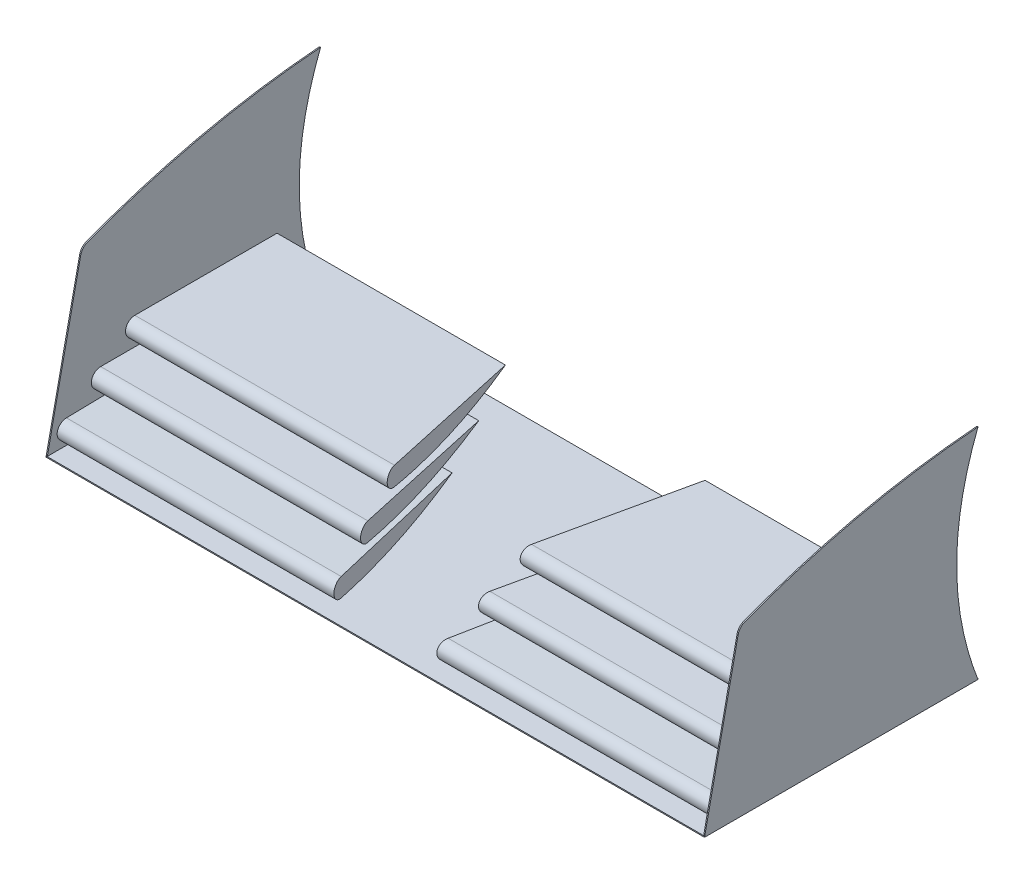
SolidWorks part; units mm, degrees
ref_plane "Front Plane" through (0, 0, 0) normal (0, 0, 1) x (1, 0, 0)
ref_plane "Top Plane" through (0, 0, 0) normal (0, 1, 0) x (1, 0, 0)
ref_plane "Right Plane" through (0, 0, 0) normal (1, 0, 0) x (0, 0, -1)
sketch "Sketch1" plane through (0, 0, 0) normal (1, 0, 0) x (0, 0, -1)
  line L1 (0, 0) -> (635, 0)
  line L2 (0, 0) -> (0, 508)
  line L3 (0, 508) -> (635, 508)
  line L4 (635, 0) -> (635, 508)
  dimension "D1" = 508
  dimension "D2" = 635
extrude "Boss-Extrude1" add sketch "Sketch1" along normal blind 2.54 from offset 762
mirror "Mirror2" about plane through (0, 0, 0) normal (1, 0, 0) of bodies 101
sketch "Sketch2" plane through (0, 0, 0) normal (1, 0, 0) x (0, 0, -1)
  line L0 (635, 508) -> (635, 0)
  spline S0 degree 2 poles (635, 508) (535.9785, 253.9497) (635, 0) knots 0 0 0 1 1 1
extrude "Cut-Extrude1" cut sketch "Sketch2" against normal through all both and the other way through all
sketch "Sketch3" plane through (0, 0, 0) normal (1, 0, 0) x (0, 0, -1)
  line L0 (0, 0) -> (78.1261, 368.5424)
  line L2 (0, 0) -> (0, 508)
  line L3 (0, 508) -> (635, 508)
  arc A0 (93.9896, 387.033) -> (78.1261, 368.5424) centre (102.9739, 363.275) ccw
  spline S0 degree 3 poles (635, 508) (448.7015, 493.2828) (268.258, 452.9341) (93.9896, 387.033) knots 0 0 0 0 0.975723 0.975723 0.975723 0.975723
  dimension "D1" = 25.4
extrude "Cut-Extrude2" cut sketch "Sketch3" against normal through all both and the other way through all
sketch "Sketch4" plane through (0, 0, 0) normal (1, 0, 0) x (0, 0, -1)
  line L0 (0, 0) -> (635, 508) construction
  line L1 (45.0812, 57.7248) -> (375.2812, 64.5745)
  line L2 (124.4174, 121.1938) -> (454.6174, 121.1938)
  line L3 (203.7537, 184.6629) -> (533.9537, 184.6629)
  arc A0 (45.0812, 57.7248) -> (45.0812, 14.405) centre (45.0812, 36.0649) ccw
  arc A1 (124.4174, 121.1938) -> (124.4174, 77.8741) centre (124.4174, 99.5339) ccw
  arc A2 (203.7537, 184.6629) -> (203.7537, 141.3431) centre (203.7537, 163.003) ccw
  spline S0 degree 2 poles (375.2812, 64.5745) (213.9845, 12.3103) (45.0812, 14.405) knots 0 0 0 1 1 1
  spline S1 degree 2 poles (454.6174, 121.1938) (292.9345, 71.3161) (124.4174, 77.8741) knots 0 0 0 1 1 1
  spline S2 degree 2 poles (203.7537, 141.3431) (373.0548, 130.6686) (533.9537, 184.6629) knots 0 0 0 1 1 1
  point P18 (368.8537, 184.6629)
  point P19 (375.2812, 64.5745)
  dimension "D1" = 38.1
  dimension "D2" = 38.1
  dimension "D3" = 330.2
  dimension "D4" = 38.1
  dimension "D5" = 330.2
  dimension "D6" = 330.2
  dimension "D7" = 101.6
  dimension "D8" = 101.6
extrude "Boss-Extrude2" add sketch "Sketch4" along normal up to body (762 mm away) and the other way up to body (764.54 mm away) separate body
sketch "Sketch6" plane through (0, 0, 0) normal (0, 1, 0) x (1, 0, 0)
  line L1 (-764.54, 0) -> (764.54, 0)
  line L2 (-764.54, 0) -> (-764.54, 635)
  line L3 (-764.54, 635) -> (764.54, 635)
  line L4 (764.54, 0) -> (764.54, 635)
extrude "Boss-Extrude3" add sketch "Sketch6" along normal blind 2.54 separate body
sketch "Sketch7" plane through (0, 184.6629, 0) normal (0, 1, 0) x (1, 0, 0)
  line L0 (-254, 635) -> (-114.3, 0)
  line L1 (764.54, 635) -> (-764.54, 635) construction
  line L2 (-764.54, 0) -> (764.54, 0) construction
  line L3 (254, 635) -> (114.3, 0)
  line L4 (0, 0) -> (0, 635) construction
  line L5 (-254, 635) -> (254, 635)
  line L6 (-114.3, 0) -> (114.3, 0)
  dimension "D1" = 114.3
  dimension "D2" = 114.3
  dimension "D3" = 254
  dimension "D4" = 254
extrude "Cut-Extrude3" cut sketch "Sketch7" against normal up to surface (182.1229 mm away) up to face at (0, 2.54, -317.351)
